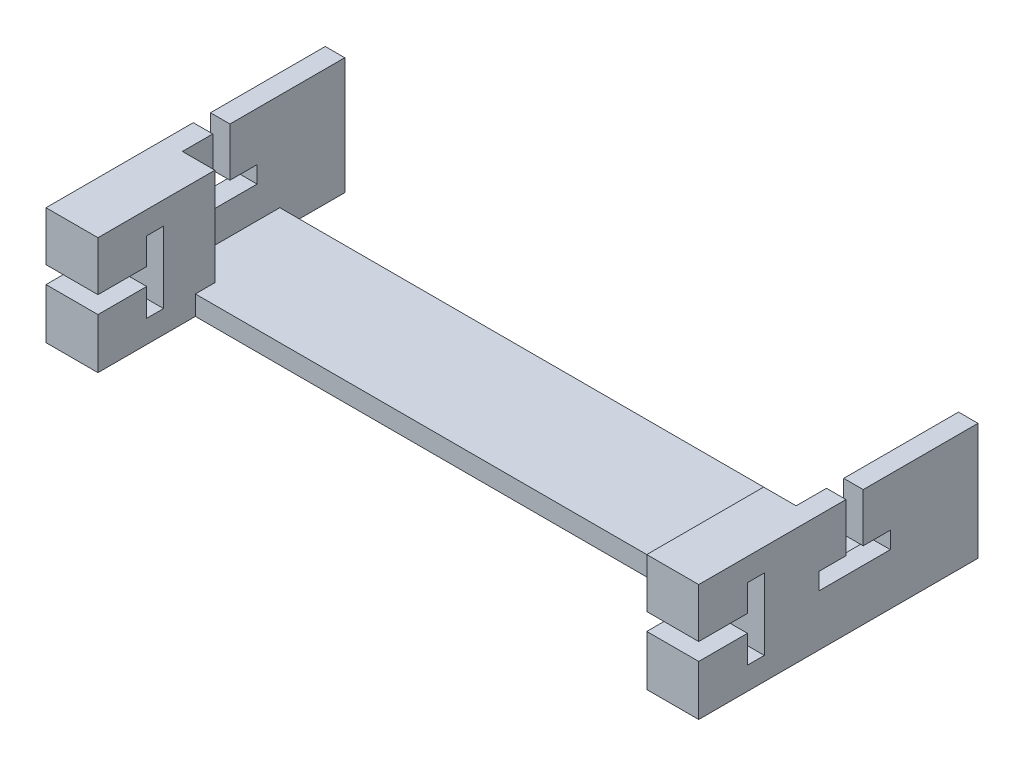
SolidWorks part; units mm, degrees
ref_plane "Front Plane" through (0, 0, 0) normal (0, 0, 1) x (1, 0, 0)
ref_plane "Top Plane" through (0, 0, 0) normal (0, 1, 0) x (1, 0, 0)
ref_plane "Right Plane" through (0, 0, 0) normal (1, 0, 0) x (0, 0, -1)
sketch "Sketch1" plane through (0, 0, 0) normal (0, 1, 0) x (1, 0, 0)
  line L1 (0, 0) -> (30, 0)
  line L2 (0, 0) -> (0, -30)
  line L3 (0, -30) -> (30, -30)
  line L4 (30, 0) -> (30, -30)
  dimension "D1" = 30
  dimension "D2" = 30
extrude "Boss-Extrude1" add sketch "Sketch1" along normal blind 6 contours L2 L1 L4 L3
sketch "Sketch2" plane through (30, 0, 0) normal (1, 0, 0) x (0, 0, -1)
  line L1 (-30, 0) -> (0, 0)
  line L2 (-30, 0) -> (-30, 36)
  line L3 (-30, 36) -> (0, 36)
  line L4 (0, 0) -> (0, 36)
  dimension "D1" = 36
extrude "Boss-Extrude2" add sketch "Sketch2" along normal blind 6 contours L2 L1 L4 L3
sketch "Sketch3" plane through (0, 0, 30) normal (0, 0, 1) x (1, 0, 0)
  line L0 (0, 6) -> (30, 6) construction
  line L5 (36, 0) -> (0, 0)
  line L6 (36, 0) -> (36, 36)
  line L7 (36, 36) -> (0, 36)
  line L8 (0, 0) -> (0, 36)
  line L9 (30, 6) -> (30, 36) construction
  dimension "D1" = 30
  dimension "D2" = 30
extrude "Boss-Extrude3" add sketch "Sketch3" along normal blind 6
sketch "Sketch4" plane through (0, 0, 0) normal (-1, 0, 0) x (0, 0, 1)
  line L1 (0, 6) -> (36, 6)
  line L2 (0, 6) -> (0, 0)
  line L3 (0, 0) -> (36, 0)
  line L4 (36, 6) -> (36, 0)
extrude "Boss-Extrude4" add sketch "Sketch4" along normal blind 165
sketch "Sketch6" plane through (0, 6, 0) normal (0, 1, 0) x (1, 0, 0)
  line L0 (-165, 0) -> (30, 0) construction
  line L1 (-165, -36) -> (-149, -36)
  line L2 (-165, -36) -> (-165, -30)
  line L3 (-165, -30) -> (-149, -30)
  line L4 (-149, -36) -> (-149, -30)
  line L5 (-159, 0) -> (-165, 0)
  line L6 (-159, 0) -> (-159, -30)
  line L7 (-159, -30) -> (-165, -30)
  line L8 (-165, 0) -> (-165, -30)
  line L10 (36, -36) -> (36, 0) construction
  line L11 (30, -30) -> (0, -30) construction
  line L12 (36, -36) -> (0, -36) construction
  line L13 (30, -30) -> (30, 0) construction
  dimension "D1" = 36
  dimension "D2" = 6
  dimension "D3" = 6
  dimension "D4" = 16
  dimension "D5" = 6
  dimension "D6" = 6
extrude "Boss-Extrude6" add sketch "Sketch6" along normal blind 30 contours L2 L1 L4 L3 | L6 L5 L8 L7
sketch "Sketch9" plane through (0, 0, 0) normal (-1, 0, 0) x (0, 0, 1)
  line L1 (30, 36) -> (36, 36)
  line L2 (30, 36) -> (30, 6)
  line L3 (30, 6) -> (36, 6)
  line L4 (36, 36) -> (36, 6)
extrude "Cut-Extrude2" cut sketch "Sketch9" against normal blind 20
sketch "Sketch10" plane through (0, 36, 0) normal (0, 1, 0) x (1, 0, 0)
  line L1 (20, -30) -> (36, -30)
  line L2 (20, -30) -> (20, -36)
  line L3 (20, -36) -> (36, -36)
  line L4 (36, -30) -> (36, -36)
  line L5 (30, 0) -> (36, 0)
  line L6 (30, 0) -> (30, -30)
  line L7 (30, -30) -> (36, -30)
  line L8 (36, 0) -> (36, -30)
sketch "Sketch11" plane through (36, 0, 0) normal (1, 0, 0) x (0, 0, -1)
  line L0 (0, 36) -> (-30, 36) construction
  line L1 (-29, 21) -> (-7, 21)
  line L2 (-29, 21) -> (-29, 15.8)
  line L3 (-29, 15.8) -> (-7, 15.8)
  line L4 (-7, 21) -> (-7, 15.8)
  line L5 (-29, 21) -> (-7, 15.8) construction
  line L6 (-29, 15.8) -> (-7, 21) construction
  line L7 (-20.65, 36) -> (-15.35, 36)
  line L8 (-20.65, 36) -> (-20.65, 21)
  line L9 (-20.65, 21) -> (-15.35, 21)
  line L10 (-15.35, 36) -> (-15.35, 21)
  line L11 (-20.65, 36) -> (-15.35, 21) construction
  line L12 (-20.65, 21) -> (-15.35, 36) construction
  line L13 (0, 0) -> (0, 36) construction
  line L14 (-36, 0) -> (-36, 36) construction
  point P0 (-18, 18.4)
  point P5 (-18, 28.5)
  dimension "D1" = 0
  dimension "D2" = 18
  dimension "D3" = 36
  dimension "D4" = 18
  dimension "D5" = 15
  dimension "D6" = 5.3
  dimension "D7" = 22
  dimension "D8" = 5.2
extrude "Cut-Extrude3" cut sketch "Sketch11" against normal blind 500 contours L8 L9 L10 L7 | L1 L4 L3 L2
ref_plane "Plane11" through (-165, 0, 0) normal (0, 0, 1) x (1, 0, 0)
sketch "Sketch13" plane through (0, 0, 36) normal (0, 0, 1) x (1, 0, 0)
  line L0 (-165, 0) -> (36, 0) construction
  line L1 (-165, 36) -> (-149, 36)
  line L2 (-165, 36) -> (-165, 0)
  line L3 (-165, 0) -> (-149, 0)
  line L4 (-149, 36) -> (-149, 0)
  line L5 (20, 36) -> (36, 36) construction
  line L6 (20, 36) -> (36, 36)
  line L7 (20, 36) -> (20, 0)
  line L8 (20, 0) -> (36, 0)
  line L9 (36, 36) -> (36, 0)
  line L10 (20, 6) -> (20, 36) construction
  dimension "D1" = 16
  dimension "D2" = 16
  dimension "D3" = 36
  dimension "D4" = 36
extrude "Boss-Extrude7" add sketch "Sketch13" along normal blind 30
sketch "Sketch16" plane through (-165, 0, 0) normal (-1, 0, 0) x (0, 0, 1)
  line L0 (66, 36) -> (66, 0) construction
  line L1 (51, 20.8) -> (66, 20.8)
  line L2 (51, 20.8) -> (51, 15.5)
  line L3 (51, 15.5) -> (66, 15.5)
  line L4 (66, 20.8) -> (66, 15.5)
  line L5 (15.35, 36) -> (0, 36) construction
  line L6 (45.8, 29) -> (51, 29)
  line L7 (45.8, 29) -> (45.8, 7)
  line L8 (45.8, 7) -> (51, 7)
  line L9 (51, 29) -> (51, 7)
  line L10 (45.8, 29) -> (51, 7) construction
  line L11 (45.8, 7) -> (51, 29) construction
  line L12 (0, 0) -> (66, 0) construction
  line L13 (66, 36) -> (20.65, 36) construction
  point P6 (48.4, 18)
  line M14 (66, 0) -> (66, 36)
  dimension "D1" = 0
  dimension "D2" = 15
  dimension "D3" = 5.3
  dimension "D4" = 22
  dimension "D5" = 0
  dimension "D6" = 5.2
  dimension "D7" = 36
  dimension "D8" = 18
  dimension "D9" = 8.5
extrude "Cut-Extrude4" cut sketch "Sketch16" against normal blind 2090 contours L9 L6 L7 L8 L2 | L2 L3 L1 M14
sketch "Sketch17" plane through (0, 0, 0) normal (0, 0, -1) x (-1, 0, 0)
  line L1 (-36, 36) -> (-30, 36)
  line L2 (-36, 36) -> (-36, 0)
  line L3 (-36, 0) -> (-30, 0)
  line L4 (-30, 36) -> (-30, 0)
  line L5 (159, 36) -> (165, 36)
  line L6 (159, 36) -> (159, 0)
  line L7 (159, 0) -> (165, 0)
  line L8 (165, 36) -> (165, 0)
  line L9 (165, 0) -> (-36, 0) construction
  line L10 (-36, 0) -> (-36, 36) construction
  line L11 (-30, 6) -> (-30, 36) construction
  line L12 (159, 36) -> (165, 36) construction
  line L13 (165, 36) -> (165, 0) construction
  line L14 (159, 36) -> (159, 6) construction
  line M9 (-36, 0) -> (165, 0)
  line M10 (165, 0) -> (165, 36)
  line M11 (165, 36) -> (159, 36)
  line M12 (159, 36) -> (159, 6)
  dimension "D1" = 0
  dimension "D2" = 0
  dimension "D3" = 0
  dimension "D4" = 0
  dimension "D5" = 0
  dimension "D6" = 0
  dimension "D7" = 0
  dimension "D8" = 0
extrude "Boss-Extrude8" add sketch "Sketch17" along normal blind 20 contours L6 M12 M9 M10 M11 | L2 L1 L4 L3
